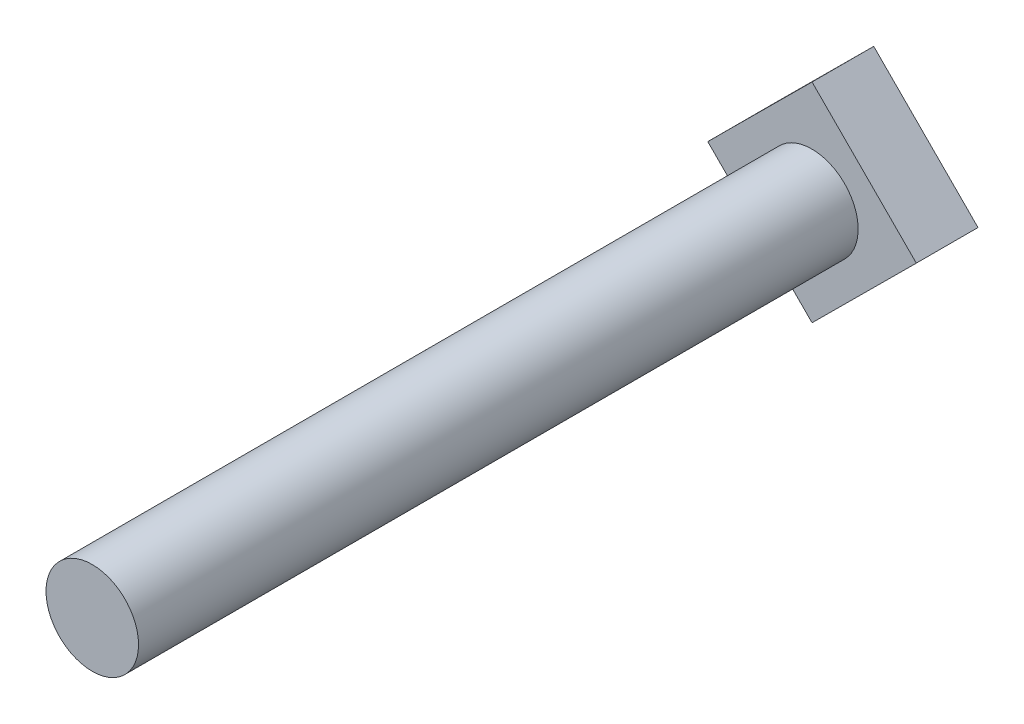
SolidWorks part; units mm, degrees
ref_plane "Plan de face" through (0, 0, 0) normal (0, 0, 1) x (1, 0, 0)
ref_plane "Plan de dessus" through (0, 0, 0) normal (0, 1, 0) x (1, 0, 0)
ref_plane "Plan de droite" through (0, 0, 0) normal (1, 0, 0) x (0, 0, -1)
sketch "Esquisse1" plane through (0, 0, 0) normal (0, 0, 1) x (1, 0, 0)
  circle A0 centre (-5.056, 0.2083) radius 45
extrude "Boss.-Extru.8" add sketch "Esquisse1" along normal blind 700
sketch "Esquisse6" plane through (0, 0, 0) normal (0, 0, -1) x (-1, 0, 0)
  line L1 (5.056, 45.2083) -> (49.7649, 0.7059)
  line L2 (-39.9435, 0) -> (4.7654, -44.5024)
  line L3 (49.7649, 0.7059) -> (4.7654, -44.5024)
  line L4 (4.925, 101.7767) -> (-96.5119, -0.1309)
  line L5 (-96.5119, -0.1309) -> (4.8963, -101.0708)
  line L6 (106.3333, 0.8368) -> (4.8963, -101.0708)
  line L7 (4.925, 101.7767) -> (106.3333, 0.8368)
  line L8 (5.056, 45.2083) -> (-39.9435, 0) construction
  circle A0 centre (5.056, 0.2083) radius 45 construction
  circle M1 centre (5.056, 0.2083) radius 45
  dimension "D1" = 40
extrude "Boss.-Extru.9" add sketch "Esquisse6" along normal blind 60 contours L1 L8 L2 L3 | L7 L4 L5 L6 M1 | L1 L3 L2 M1 | L8 M1
